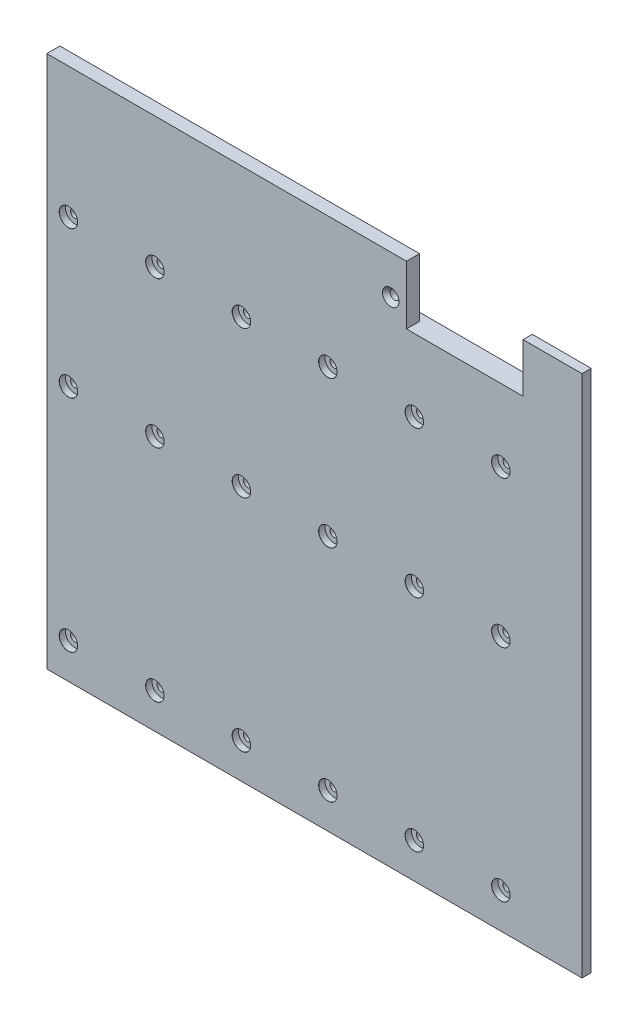
SolidWorks part; units mm, degrees
ref_plane "Plan de face" through (0, 0, 0) normal (0, 0, 1) x (1, 0, 0)
ref_plane "Plan de dessus" through (0, 0, 0) normal (0, 1, 0) x (1, 0, 0)
ref_plane "Plan de droite" through (0, 0, 0) normal (1, 0, 0) x (0, 0, -1)
sketch "Esquisse1" plane through (0, 0, 0) normal (0, 0, 1) x (1, 0, 0)
  line L1 (-204.25, -90.5) -> (204.25, -90.5)
  line L2 (-204.25, -90.5) -> (-204.25, 90.5)
  line L3 (-204.25, 90.5) -> (204.25, 90.5)
  line L4 (204.25, -90.5) -> (204.25, 90.5)
  line L5 (-204.25, -90.5) -> (204.25, 90.5) construction
  line L6 (-204.25, 90.5) -> (204.25, -90.5) construction
  point P0 (0, 0)
  dimension "D1" = 181
  dimension "D2" = 408.5
extrude "Boss.-Extru.1" add sketch "Esquisse1" along normal blind 8 contours L3 L4 L1 L2
hole_wizard "Chambrage pour vis à tête ronde bombée M31" positions "Esquisse2" profile "Esquisse3" counterbore size "M3" standard "Ansi Metric" end condition through all
sketch "Esquisse2" plane through (0, 0, 8) normal (0, 0, 1) x (1, 0, 0)
  point P0 (-156.75, 63)
  point P3 (-156.75, 7)
  point P6 (-156.75, -77)
sketch "Esquisse3" plane through (-156.75, 63, 8) normal (1, 0, 0) x (0, -1, 0)
  line L0 (0, 0) -> (0, 8)
  line L1 (0, 8) -> (1.6, 8)
  line L3 (1.6, 8) -> (1.6, 2.4)
  line L4 (3.5, 2.4) -> (1.6, 2.4)
  line L5 (3.5, 2.4) -> (3.5, 0.025)
  line L6 (3.5, 0.025) -> (3.525, 0)
  line L7 (3.525, 0) -> (0, 0)
  line L8 (-3.5, 0.025) -> (-3.525, 0) construction
  line L11 (0, -6.35) -> (0, 107.95) construction
  dimension "Diamètre du perçage jusqu'au prochain" = 3.2
  dimension "Profondeur du perçage jusqu'au prochain" = 8
  dimension "Diamètre du chambrage" = 7
  dimension "Profondeur du chambrage" = 2.4
  dimension "Diamètre du fraisage entrant" = 7.05
  dimension "Angle du fraisage entrant" = 90
pattern_linear "Répétition linéaire1" count 11 spacing 33 along (1, 0, 0) of "Chambrage pour vis à tête ronde bombée M31"
sketch "Esquisse4" plane through (0, 90.5, 0) normal (0, 1, 0) x (1, 0, 0)
  line L0 (-204.25, 0) -> (204.25, 0) construction
  line L1 (-204.25, 0) -> (-181.75, 0)
  line L2 (-204.25, 0) -> (-204.25, -4.5)
  line L3 (-204.25, -4.5) -> (-181.75, -4.5)
  line L4 (-181.75, 0) -> (-181.75, -4.5)
  line L5 (-204.25, -8) -> (204.25, -8) construction
  line L7 (0, -4.4) -> (0, 4.4) construction
  line L8 (181.75, 0) -> (181.75, -4.5)
  line L9 (204.25, -4.5) -> (181.75, -4.5)
  line L10 (204.25, 0) -> (204.25, -4.5)
  line L11 (204.25, 0) -> (181.75, 0)
  line L12 (-204.25, -8) -> (-204.25, 0) construction
  dimension "D1" = 3.5
  dimension "D3" = 22.5
extrude "Enlèv. mat.-Extru.1" cut sketch "Esquisse4" against normal up to surface (181 mm away) up to face at (0, -90.5, 4)
sketch "Esquisse5" plane through (0, 0, 8) normal (0, 0, 1) x (1, 0, 0)
  line L1 (-204.25, 90.5) -> (-181.75, 90.5)
  line L2 (-204.25, 90.5) -> (-204.25, 109.225)
  line L3 (-204.25, 109.225) -> (-181.75, 109.225)
  line L4 (-181.75, 90.5) -> (-181.75, 109.225)
  line L6 (-204.25, 90.5) -> (204.25, 90.5) construction
  dimension "D1" = 22.5
  dimension "D2" = 18.725
extrude "Boss.-Extru.2" add sketch "Esquisse5" against normal up to surface (3.5 mm away) up to face at (-193, 0, 4.5)
mirror "Symétrie1" about plane through (0, 0, 0) normal (1, 0, 0) of "Boss.-Extru.2"
sketch "Esquisse7" plane through (0, 0, 8) normal (0, 0, 1) x (1, 0, 0)
  line L0 (-181.75, 90.5) -> (181.75, 90.5) construction
  line L1 (-137.25, 90.5) -> (137.25, 90.5)
  line L2 (-137.25, 90.5) -> (-137.25, 112.875)
  line L3 (-137.25, 112.875) -> (137.25, 112.875)
  line L4 (137.25, 90.5) -> (137.25, 112.875)
  line L5 (137.75, 91) -> (137.75, 116.55) construction
  line L6 (-137.75, 91) -> (-137.75, 116.55) construction
  line L7 (-124.75, 113.375) -> (-137.75, 113.375) construction
  dimension "D1" = 0.5
  dimension "D2" = 0.5
  dimension "D3" = 0.5
extrude "Boss.-Extru.3" add sketch "Esquisse7" against normal blind 5
hole_wizard "Fraisage pour vis à tête fraisée M31" positions "Esquisse8" profile "Esquisse9" countersink size "M3" standard "Ansi Metric" end condition through all
sketch "Esquisse8" plane through (0, 0, 8) normal (0, 0, 1) x (1, 0, 0)
  point P0 (-131.25, 98)
  point P3 (131.25, 98)
sketch "Esquisse9" plane through (-131.25, 98, 8) normal (1, 0, 0) x (0, -1, 0)
  line L0 (0, 0) -> (0, 8)
  line L1 (0, 8) -> (1.7, 8)
  line L2 (1.7, 8) -> (1.7, 1.45)
  line L3 (1.7, 1.45) -> (3.15, 0)
  line L5 (3.15, 0) -> (0, 0)
  line L6 (-1.7, 1.45) -> (-3.15, 0) construction
  line L11 (0, -6.35) -> (0, 107.95) construction
  dimension "Diamètre du perçage jusqu'au prochain" = 3.4
  dimension "Profondeur du perçage jusqu'au prochain" = 8
  dimension "Diamètre du fraisage entrant" = 6.3
  dimension "Angle du fraisage entrant" = 90
sketch "Esquisse10" plane through (0, 0, 0) normal (0, 0, -1) x (-1, 0, 0)
  line L0 (-137.25, 112.875) -> (137.25, 112.875) construction
  line L1 (204.25, -90.5) -> (0, -90.5)
  line L2 (204.25, -90.5) -> (204.25, 112.875)
  line L3 (204.25, 112.875) -> (0, 112.875)
  line L4 (0, -90.5) -> (0, 112.875)
extrude "Enlèv. mat.-Extru.2" cut sketch "Esquisse10" against normal blind 10
